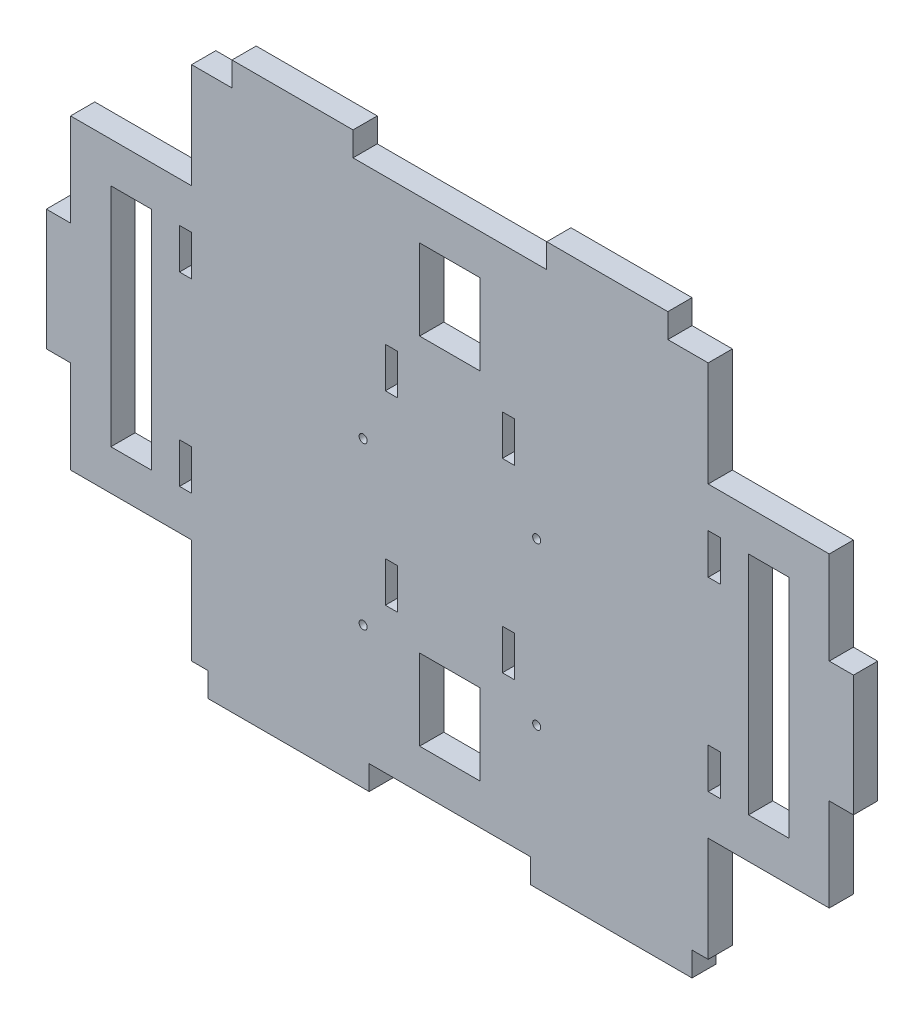
SolidWorks part; units mm, degrees
ref_plane "Plan de face" through (0, 0, 0) normal (0, 0, 1) x (1, 0, 0)
ref_plane "Plan de dessus" through (0, 0, 0) normal (0, 1, 0) x (1, 0, 0)
ref_plane "Plan de droite" through (0, 0, 0) normal (1, 0, 0) x (0, 0, -1)
sketch "Esquisse1" plane through (0, 0, 0) normal (0, 0, 1) x (1, 0, 0)
  line L0 (0, 64) -> (0, -64) construction
  line L1 (-94, 64) -> (-94, 15)
  line L2 (-94, 64) -> (-54, 64)
  line L3 (-94, -64) -> (-60, -64)
  line L4 (94, 64) -> (94, 15)
  line L5 (-94, 64) -> (94, -64) construction
  line L6 (-94, -64) -> (94, 64) construction
  line L7 (-24, 64) -> (24, 64)
  line L8 (54, 64) -> (54, 70)
  line L9 (-54, 64) -> (-54, 70)
  line L10 (-54, 70) -> (-24, 70)
  line L11 (-20, -64) -> (20, -64)
  line L12 (-24, 64) -> (-24, 70)
  line L13 (24, 64) -> (24, 70)
  line L14 (54, 70) -> (24, 70)
  line L15 (54, 64) -> (94, 64)
  line L16 (94, 15) -> (100, 15)
  line L17 (-94, 15) -> (-100, 15)
  line L18 (94, -15) -> (94, -64)
  line L19 (-94, -15) -> (-100, -15)
  line L20 (-100, 15) -> (-100, -15)
  line L21 (100, 15) -> (100, -15)
  line L22 (94, -15) -> (100, -15)
  line L23 (-94, -15) -> (-94, -64)
  line L24 (20, -64) -> (20, -70)
  line L25 (-60, -64) -> (-60, -70)
  line L26 (-60, -70) -> (-20, -70)
  line L27 (-20, -64) -> (-20, -70)
  line L28 (60, -70) -> (20, -70)
  line L29 (60, -64) -> (60, -70)
  line L30 (60, -64) -> (94, -64)
  point P0 (0, 0)
  dimension "D1" = 188
  dimension "D2" = 128
  dimension "D3" = 40
  dimension "D4" = 6
  dimension "D5" = 30
  dimension "D6" = 30
  dimension "D7" = 6
  dimension "D8" = 49
  dimension "D9" = 40
  dimension "D10" = 34
  dimension "D11" = 6
extrude "Boss.-Extru.3" add sketch "Esquisse1" along normal blind 6 contours L1 L17 L20 L19 L23 L3 L25 L26 L27 L11 L24 L28 L29 L30 L18 L22 L21 L16 L4 L15 L8 L14 L13 L7 L12 L10 L9 L2
sketch "Esquisse2" plane through (0, 0, 6) normal (0, 0, 1) x (1, 0, 0)
  line L0 (0, 64) -> (0, -64) construction
  line L1 (-94, -15) -> (-94, -64) construction
  line L2 (-67, -18) -> (-64, -18)
  line L3 (-67, -18) -> (-67, -28)
  line L4 (-67, -28) -> (-64, -28)
  line L5 (-67, 18) -> (-64, 18)
  line L6 (-67, 18) -> (-67, 28)
  line L7 (-67, 28) -> (-64, 28)
  line L8 (-64, 18) -> (-64, 28)
  line L9 (-16, -28) -> (-13, -28)
  line L10 (-16, -28) -> (-16, -18)
  line L11 (-16, -18) -> (-13, -18)
  line L12 (-13, -28) -> (-13, -18)
  line L13 (-16, 28) -> (-13, 28)
  line L14 (-16, 28) -> (-16, 18)
  line L15 (-16, 18) -> (-13, 18)
  line L16 (-13, 28) -> (-13, 18)
  line L20 (-64, -18) -> (-64, -28)
  line L21 (-94, -64) -> (-60, -64) construction
  line L22 (-94, 64) -> (-94, 15) construction
  line L23 (-94, 64) -> (-54, 64) construction
  line L24 (-20, -64) -> (20, -64) construction
  line L25 (-24, 64) -> (24, 64) construction
  line L26 (64, -18) -> (64, -28)
  line L27 (13, 28) -> (13, 18)
  line L28 (16, 18) -> (13, 18)
  line L29 (16, 28) -> (16, 18)
  line L30 (16, 28) -> (13, 28)
  line L31 (13, -28) -> (13, -18)
  line L32 (16, -18) -> (13, -18)
  line L33 (16, -28) -> (16, -18)
  line L34 (16, -28) -> (13, -28)
  line L35 (64, 18) -> (64, 28)
  line L36 (67, 28) -> (64, 28)
  line L37 (67, 18) -> (67, 28)
  line L38 (67, 18) -> (64, 18)
  line L39 (67, -28) -> (64, -28)
  line L40 (67, -18) -> (67, -28)
  line L41 (67, -18) -> (64, -18)
  dimension "D1" = 27
  dimension "D2" = 36
  dimension "D3" = 10
  dimension "D4" = 27
  dimension "D5" = 36
  dimension "D6" = 36
  dimension "D7" = 48
  dimension "D8" = 48
  dimension "D9" = 3
  dimension "D10" = 3
  dimension "D11" = 36
  dimension "D12" = 36
  dimension "D13" = 36
  dimension "D14" = 10
  dimension "D15" = 3
  dimension "D16" = 3
extrude "Enlèv. mat.-Extru.1" cut sketch "Esquisse2" against normal blind 10
sketch "Esquisse3" plane through (0, 0, 6) normal (0, 0, 1) x (1, 0, 0)
  line L0 (64, -64) -> (64, -38)
  line L1 (60, -64) -> (94, -64) construction
  line L2 (64, -38) -> (94, -38)
  line L3 (94, -15) -> (94, -64) construction
  line L4 (94, -38) -> (94, -64)
  line L5 (94, -64) -> (64, -64)
  line L6 (-100, 0) -> (100, 0) construction
  line L7 (-100, 15) -> (-100, -15) construction
  line L8 (100, 15) -> (100, -15) construction
  line L9 (0, 64) -> (0, -64) construction
  line L10 (-24, 64) -> (24, 64) construction
  line L11 (-20, -64) -> (20, -64) construction
  line L12 (-94, -64) -> (-64, -64)
  line L13 (-94, -38) -> (-94, -64)
  line L14 (-64, -38) -> (-94, -38)
  line L15 (-64, -64) -> (-64, -38)
  line L16 (-64, 64) -> (-64, 38)
  line L17 (-64, 38) -> (-94, 38)
  line L18 (-94, 38) -> (-94, 64)
  line L19 (-94, 64) -> (-64, 64)
  line L20 (94, 64) -> (64, 64)
  line L21 (94, 38) -> (94, 64)
  line L22 (64, 38) -> (94, 38)
  line L23 (64, 64) -> (64, 38)
  dimension "D1" = 30
  dimension "D2" = 26
extrude "Enlèv. mat.-Extru.2" cut sketch "Esquisse3" against normal blind 6
sketch "Esquisse4" plane through (0, 0, 0) normal (0, 0, -1) x (-1, 0, 0)
  line L0 (0, -64) -> (0, -54) construction
  line L1 (-7.5, -34) -> (7.5, -34)
  line L2 (-7.5, -34) -> (-7.5, -54)
  line L3 (-7.5, -54) -> (7.5, -54)
  line L4 (7.5, -34) -> (7.5, -54)
  line L5 (20, -64) -> (-20, -64) construction
  line L6 (24, 64) -> (-24, 64) construction
  line L7 (-100, 0) -> (100, 0) construction
  line L8 (-100, 15) -> (-100, -15) construction
  line L9 (100, 15) -> (100, -15) construction
  line L10 (0, 64) -> (0, 54) construction
  line L11 (7.5, 34) -> (7.5, 54)
  line L12 (-7.5, 54) -> (7.5, 54)
  line L13 (-7.5, 34) -> (-7.5, 54)
  line L14 (-7.5, 34) -> (7.5, 34)
  dimension "D1" = 15
  dimension "D2" = 20
  dimension "D3" = 10
  dimension "D4" = 10
  dimension "D5" = 118
extrude "Enlèv. mat.-Extru.3" cut sketch "Esquisse4" against normal blind 6
sketch "Esquisse5" plane through (0, 0, 0) normal (0, 0, -1) x (-1, 0, 0)
  line L0 (-94, -15) -> (-94, -38) construction
  line L1 (-84, 28) -> (-74, 28)
  line L2 (-84, 28) -> (-84, -28)
  line L3 (-84, -28) -> (-74, -28)
  line L4 (-74, 28) -> (-74, -28)
  line L5 (74, 28) -> (84, 28)
  line L6 (74, 28) -> (74, -28)
  line L7 (74, -28) -> (84, -28)
  line L8 (84, 28) -> (84, -28)
  line L9 (-94, -38) -> (-64, -38) construction
  line L10 (64, -38) -> (94, -38) construction
  line L11 (94, -15) -> (94, -38) construction
  point P8 (-94, -26.5)
  dimension "D1" = 10
  dimension "D2" = 56
  dimension "D3" = 10
  dimension "D4" = 10
  dimension "D5" = 10
  dimension "D6" = 10
  dimension "D7" = 10
  dimension "D8" = 56
extrude "Enlèv. mat.-Extru.4" cut sketch "Esquisse5" against normal blind 6
sketch "Esquisse6" plane through (0, 0, 0) normal (0, 0, -1) x (-1, 0, 0)
  line L0 (21.5, -70) -> (21.5, 70) construction
  line L1 (60, -70) -> (20, -70) construction
  line L2 (54, 70) -> (24, 70) construction
  line L3 (0, -64) -> (0, 64) construction
  line L4 (20, -64) -> (-20, -64) construction
  line L5 (24, 64) -> (-24, 64) construction
  circle A0 centre (21.5, -35) radius 1
  circle A1 centre (21.5, 5) radius 1
  circle A2 centre (-21.5, 5) radius 1
  circle A3 centre (-21.5, -35) radius 1
  dimension "D1" = 2
  dimension "D2" = 2
  dimension "D3" = 21.5
  dimension "D4" = 40
  dimension "D5" = 35
extrude "Enlèv. mat.-Extru.5" cut sketch "Esquisse6" against normal through all
sketch "Esquisse7" plane through (0, 0, 0) normal (0, 0, -1) x (-1, 0, 0)
  line L0 (0, -64) -> (0, 64) construction
  line L1 (13.5, -38) -> (29.5, -38)
  line L2 (13.5, -38) -> (13.5, -32)
  line L3 (13.5, -32) -> (29.5, -32)
  line L4 (29.5, -38) -> (29.5, -32)
  line L5 (20, -64) -> (-20, -64) construction
  line L6 (24, 64) -> (-24, 64) construction
  line L7 (22, -15) -> (28, -15) construction
  line L8 (29.5, 8) -> (29.5, 2)
  line L9 (13.5, 2) -> (29.5, 2)
  line L10 (13.5, 8) -> (13.5, 2)
  line L11 (13.5, 8) -> (29.5, 8)
  line L36 (-13.5, 8) -> (-29.5, 8)
  line L37 (-13.5, 8) -> (-13.5, 2)
  line L38 (-13.5, 2) -> (-29.5, 2)
  line L39 (-29.5, 8) -> (-29.5, 2)
  line L40 (-29.5, -38) -> (-29.5, -32)
  line L41 (-13.5, -32) -> (-29.5, -32)
  line L42 (-13.5, -38) -> (-13.5, -32)
  line L43 (-13.5, -38) -> (-29.5, -38)
  circle A0 centre (21.5, -35) radius 1 construction
  dimension "D3" = 3
  dimension "D5" = 20
  dimension "D1" = 16
  dimension "D2" = 6
  dimension "D4" = 8
extrude "Enlèv. mat.-Extru.6" cut sketch "Esquisse7" against normal blind 1
